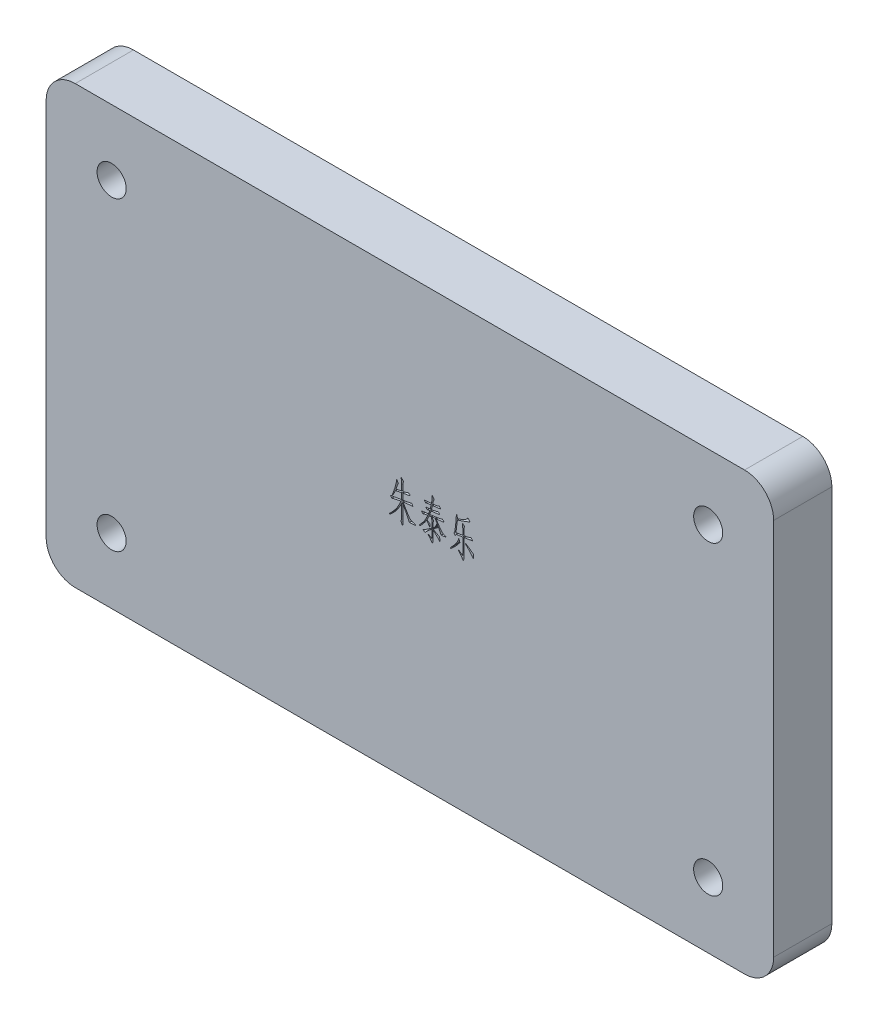
SolidWorks part; units mm, degrees
ref_plane "前视基准面" through (0, 0, 0) normal (0, 0, 1) x (1, 0, 0)
ref_plane "上视基准面" through (0, 0, 0) normal (0, 1, 0) x (1, 0, 0)
ref_plane "右视基准面" through (0, 0, 0) normal (1, 0, 0) x (0, 0, -1)
other "Configuration Table"
sketch "草图1" plane through (0, 0, 0) normal (0, 0, 1) x (1, 0, 0)
  line L1 (-22.0774, 16.8712) -> (437.9226, 16.8712)
  line L2 (-42.0774, -3.1288) -> (-42.0774, -263.1288)
  line L3 (-22.0774, -283.1288) -> (437.9226, -283.1288)
  line L4 (457.9226, -3.1288) -> (457.9226, -263.1288)
  circle A0 centre (2.9226, -28.1288) radius 10
  circle A1 centre (2.9226, -238.1288) radius 10
  circle A2 centre (412.9226, -238.1288) radius 10
  circle A3 centre (412.9226, -28.1288) radius 10
  arc A4 (-42.0774, -3.1288) -> (-22.0774, 16.8712) centre (-22.0774, -3.1288) cw
  arc A5 (-22.0774, -283.1288) -> (-42.0774, -263.1288) centre (-22.0774, -263.1288) cw
  arc A6 (457.9226, -3.1288) -> (437.9226, 16.8712) centre (437.9226, -3.1288) ccw
  arc A7 (437.9226, -283.1288) -> (457.9226, -263.1288) centre (437.9226, -263.1288) ccw
  text T0 "朱泰乐" font "汉仪长仿宋体" height 20.0547
  point P14 (-42.0774, 16.8712)
  point P17 (-42.0774, -283.1288)
  point P20 (457.9226, 16.8712)
  dimension "D3" = 45
  dimension "D10" = 210
  dimension "D11" = 20
  dimension "D12" = 20
  dimension "D13" = 20
  dimension "D14" = 20
  dimension "D1" = 300
  dimension "D2" = 500
  dimension "D4" = 45
  dimension "D5" = 410
  dimension "D6" = 45
  dimension "D7" = 45
  dimension "D8" = 45
  dimension "D9" = 45
extrude "凸台-拉伸1" add sketch "草图1" along normal blind 40
